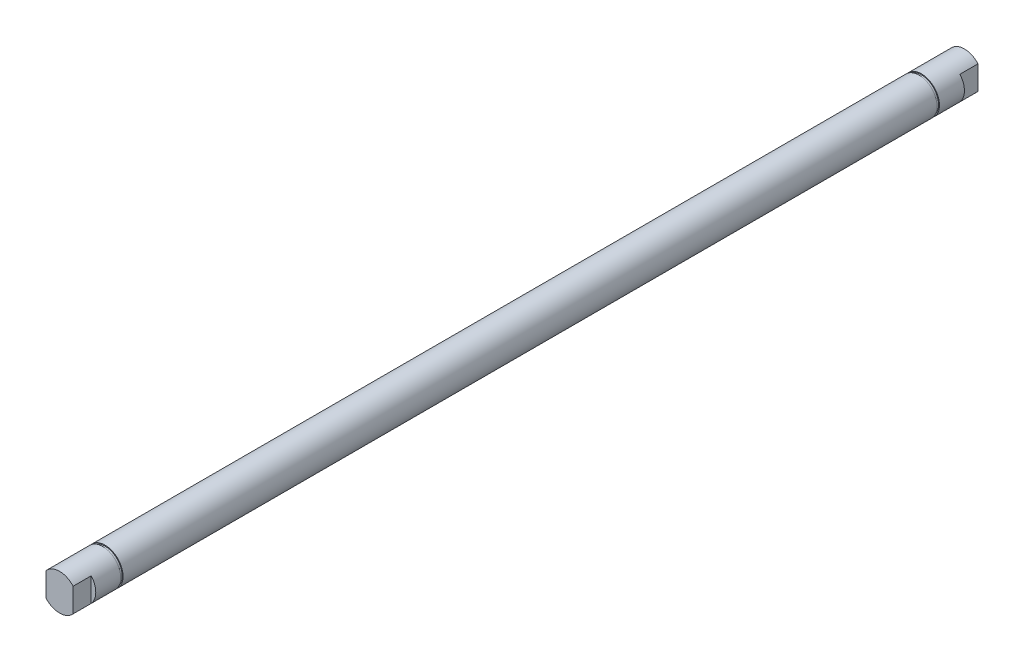
SolidWorks part; units mm, degrees
ref_plane "前视基准面" through (0, 0, 0) normal (0, 0, 1) x (1, 0, 0)
ref_plane "上视基准面" through (0, 0, 0) normal (0, 1, 0) x (1, 0, 0)
ref_plane "右视基准面" through (0, 0, 0) normal (1, 0, 0) x (0, 0, -1)
sketch "草图1" plane through (0, 0, 0) normal (0, 0, 1) x (1, 0, 0)
  circle A0 centre (0, 0) radius 10
  dimension "D1" = 20
extrude "凸台-拉伸1" add sketch "草图1" along normal mid plane 500
sketch "草图2" plane through (0, 0, 250) normal (0, 0, 1) x (1, 0, 0)
  line L0 (0, 0) -> (10, 0) construction
  circle A0 centre (0, 0) radius 10
  circle A2 centre (0, 0) radius 10 construction
  point P2 (10, 0)
  dimension "D1" = 20
ref_plane "基准面1" through (10, 0, 250) normal (0, 1, 0) x (1, 0, 0)
sketch "草图3" plane through (100, 0, 250) normal (0, 1, 0) x (0, 0, -1)
  line L0 (0, 100) -> (33.5023, 100) construction
  line L2 (23.8, 90) -> (25.1, 90)
  line L3 (23.8, 90) -> (23.8, 90.5)
  line L4 (23.8, 90.5) -> (25.1, 90.5)
  line L5 (25.1, 90) -> (25.1, 90.5)
  line L6 (0, 110) -> (0, 90) construction
  dimension "D1" = 1.3
  dimension "D2" = 9.5
  dimension "D3" = 25.1
revolve "切除-旋转1" cut sketch "草图3" angle 360 about L0
other "轴卡簧特征库<1>"
sketch "草图4" plane through (0, 0, -250) normal (0, 0, -1) x (-1, 0, 0)
  line L1 (-7.5, 25.5006) -> (7.5, 25.5006)
  line L2 (-7.5, 25.5006) -> (-7.5, -25.5006)
  line L3 (-7.5, -25.5006) -> (7.5, -25.5006)
  line L4 (7.5, 25.5006) -> (7.5, -25.5006)
  line L5 (-7.5, 25.5006) -> (7.5, -25.5006) construction
  line L6 (-7.5, -25.5006) -> (7.5, 25.5006) construction
  point P0 (0, 0)
  dimension "D1" = 15
extrude "切除-拉伸1" cut sketch "草图4" against normal blind 10 flip side to cut
mirror "镜向1" about plane through (0, 0, 0) normal (0, 0, 1) of "切除-拉伸1", "切除-旋转1"
